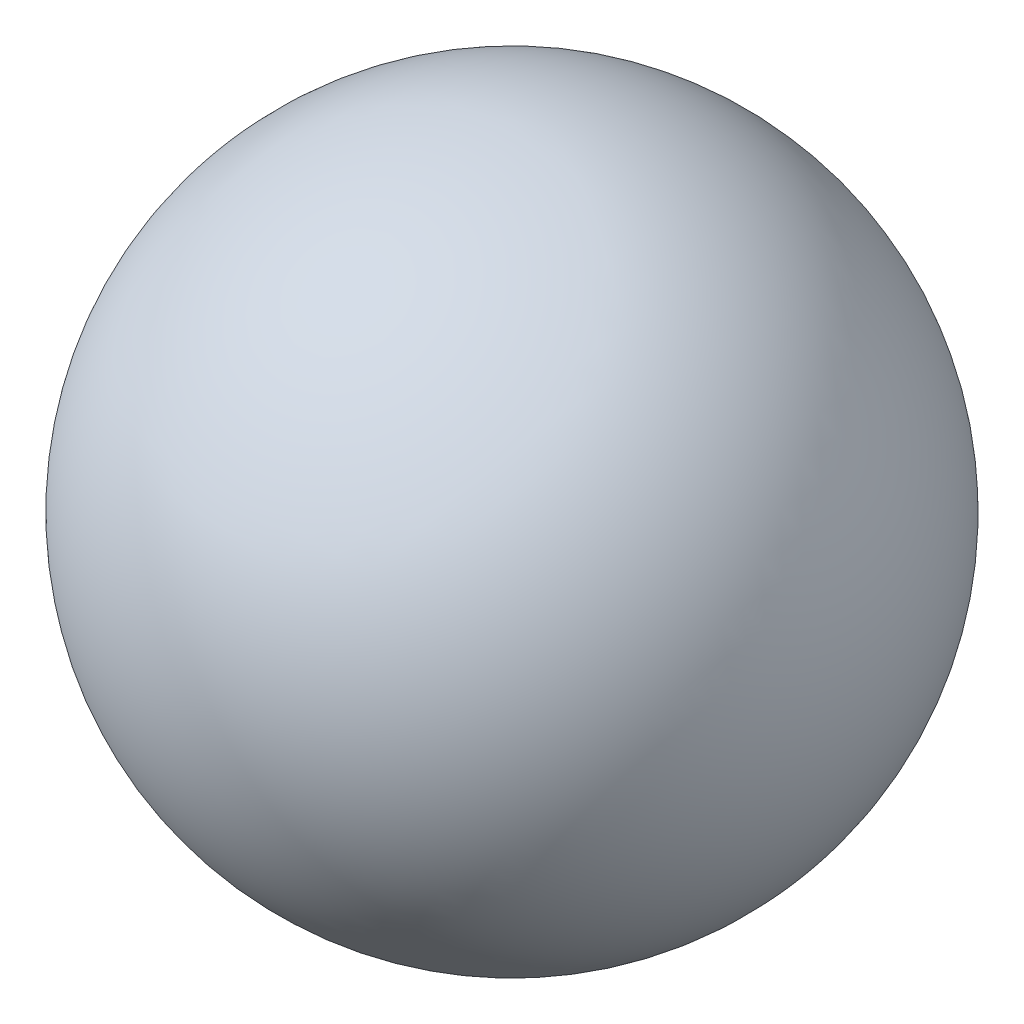
SolidWorks part; units mm, degrees
ref_plane "Front Plane" through (0, 0, 0) normal (0, 0, 1) x (1, 0, 0)
ref_plane "Top Plane" through (0, 0, 0) normal (0, 1, 0) x (1, 0, 0)
ref_plane "Right Plane" through (0, 0, 0) normal (1, 0, 0) x (0, 0, -1)
ref_plane "Plane1" through (0, 0, 0) normal (0, 0, -1) x (-1, 0, 0)
sketch "Sketch1" plane through (0, 0, 0) normal (0, 0, -1) x (-1, 0, 0)
  line L0 (2.7799, 1.605) -> (4.0941, 2.3638)
  line L1 (3.1965, 1.8455) -> (3.7656, 2.1741) construction
  arc A0 (4.0941, 2.3638) -> (2.7799, 1.605) centre (3.437, 1.9844) ccw
revolve "Revolve1" add sketch "Sketch1" angle 360 about L1
